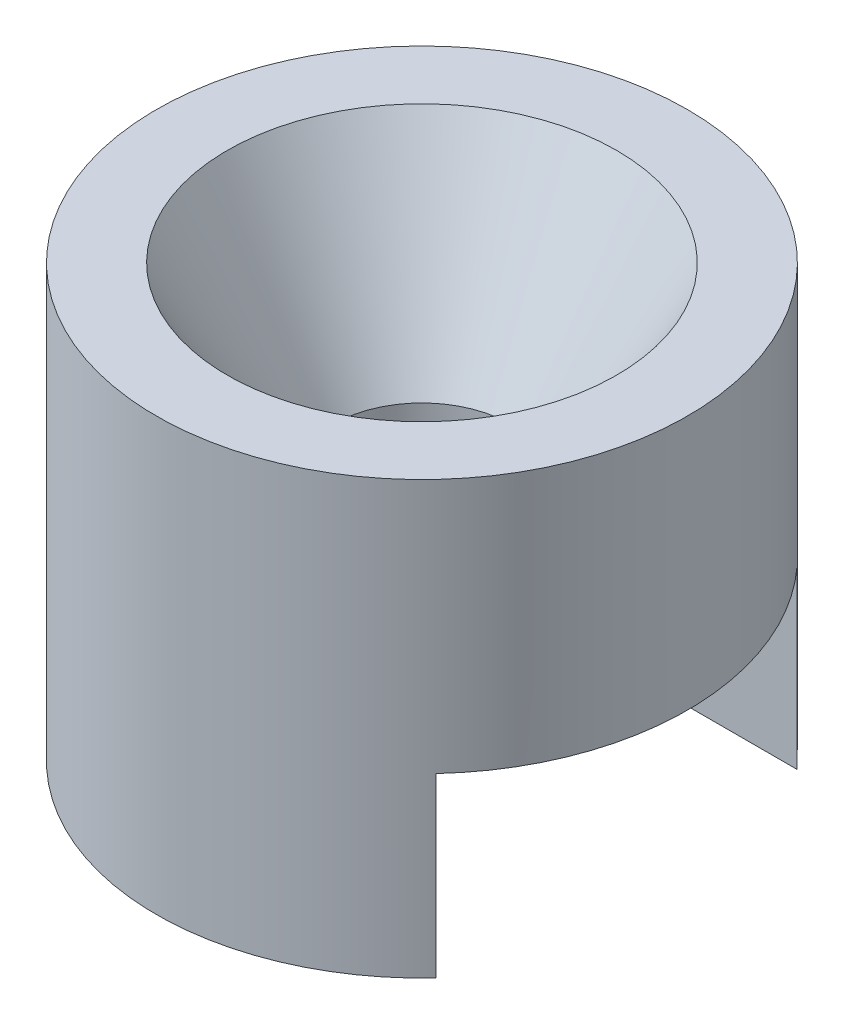
SolidWorks part; units mm, degrees
ref_plane "前视" through (0, 0, 0) normal (0, 0, 1) x (1, 0, 0)
ref_plane "上视" through (0, 0, 0) normal (0, 1, 0) x (1, 0, 0)
ref_plane "右视" through (0, 0, 0) normal (1, 0, 0) x (0, 0, -1)
sketch "Sketch7" plane through (0, 0, 0) normal (0, 1, 0) x (1, 0, 0)
  circle A0 centre (0, 0) radius 7.5
  circle A1 centre (0, 0) radius 2.5
  dimension "D1" = 15
  dimension "D2" = 5
extrude "Boss-Extrude3" add sketch "Sketch7" along normal blind 2
sketch "Sketch8" plane through (0, 0, 0) normal (0, -1, 0) x (1, 0, 0)
  line L0 (-5.4991, 5.1) -> (5.4991, 5.1)
  line L1 (-5.1, -5.1) -> (5.1, -5.1) construction
  line L2 (-5.1, -5.1) -> (-5.1, 5.1) construction
  line L3 (-5.1, 5.1) -> (5.1, 5.1) construction
  line L4 (5.1, -5.1) -> (5.1, 5.1) construction
  line L5 (-5.1, -5.1) -> (5.1, 5.1) construction
  line L6 (-5.1, 5.1) -> (5.1, -5.1) construction
  line L7 (-5.4991, -5.1) -> (5.4991, -5.1)
  circle A0 centre (0, 0) radius 7.5 construction
  arc A1 (-5.4991, 5.1) -> (5.4991, 5.1) centre (0, 0) cw
  arc A2 (-5.4991, -5.1) -> (5.4991, -5.1) centre (0, 0) ccw
  point P0 (0, 0)
  circle M1 centre (0, 0) radius 7.5
  dimension "D1" = 10.2
extrude "Boss-Extrude4" add sketch "Sketch8" along normal blind 5 contours L0 M1 | L7 M1
sketch "Sketch9" plane through (0, 0, 0) normal (0, 0, 1) x (1, 0, 0)
  line L0 (2.5, 2) -> (5.5, 7.1962)
  line L1 (5.5, 7.1962) -> (7.5, 7.1962)
  line L2 (7.5, 7.1962) -> (7.5, 2)
  line L3 (7.5, 2) -> (2.5, 2)
  line L4 (0, 0) -> (0, 8.6079) construction
  dimension "D2" = 60
  dimension "D3" = 5.5
revolve "Revolve1" add sketch "Sketch9" angle 360 about L4
